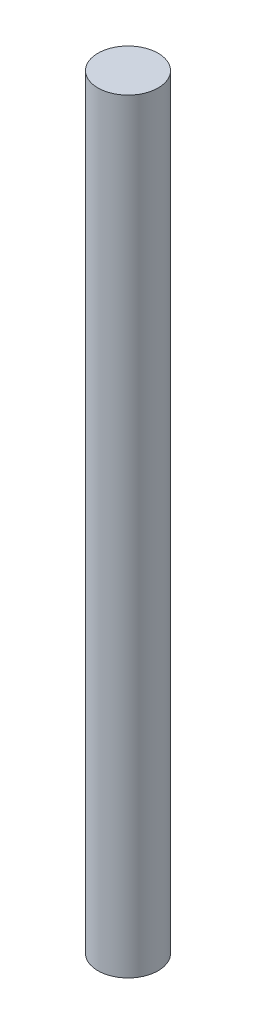
SolidWorks part; units mm, degrees
ref_plane "Front Plane" through (0, 0, 0) normal (0, 0, 1) x (1, 0, 0)
ref_plane "Top Plane" through (0, 0, 0) normal (0, 1, 0) x (1, 0, 0)
ref_plane "Right Plane" through (0, 0, 0) normal (1, 0, 0) x (0, 0, -1)
sketch "Sketch1" plane through (0, 0, 0) normal (0, 1, 0) x (1, 0, 0)
  circle A0 centre (0, 0) radius 2
extrude "Boss-Extrude1" add sketch "Sketch1" along normal blind 50.8
